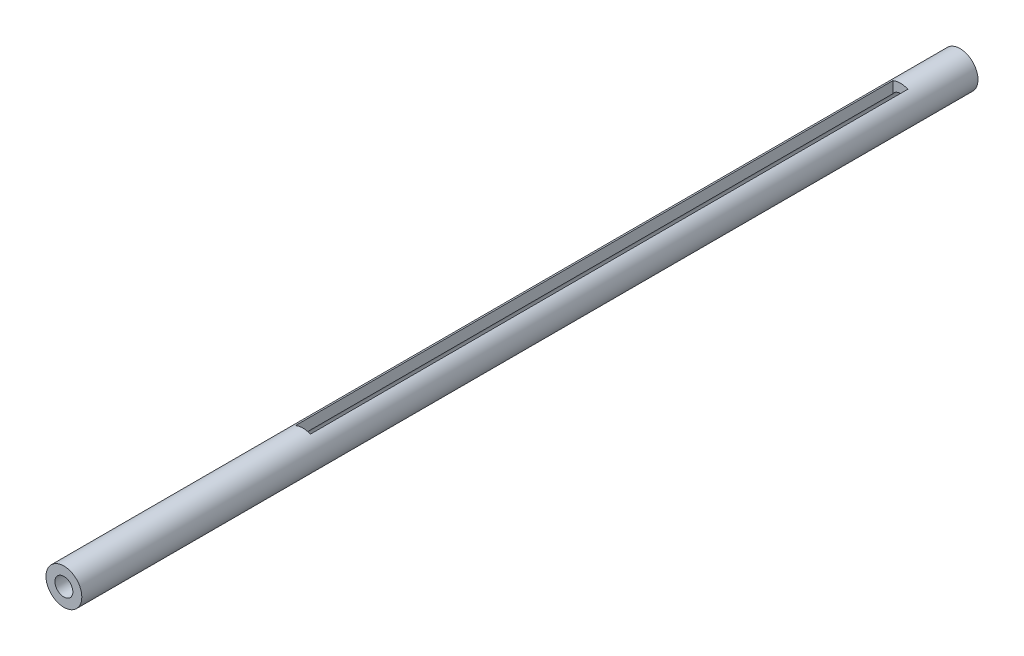
SolidWorks part; units mm, degrees
ref_plane "Front Plane" through (0, 0, 0) normal (0, 0, 1) x (1, 0, 0)
ref_plane "Top Plane" through (0, 0, 0) normal (0, 1, 0) x (1, 0, 0)
ref_plane "Right Plane" through (0, 0, 0) normal (1, 0, 0) x (0, 0, -1)
sketch "Sketch1" plane through (0, 0, 0) normal (0, 0, 1) x (1, 0, 0)
  circle A0 centre (0, 0) radius 1.5
  circle A1 centre (0, 0) radius 3
  dimension "D1" = 3
  dimension "D2" = 6
extrude "Boss-Extrude1" add sketch "Sketch1" along normal blind 150
sketch "Sketch2" plane through (0, 0, 0) normal (0, 1, 0) x (1, 0, 0)
  line L0 (-1.25, 110) -> (1.25, 110)
  line L1 (-1.25, 110) -> (-1.25, -110)
  line L2 (1.25, 110) -> (1.25, -110)
  line L3 (-1.25, -110) -> (1.25, -110)
  line L4 (-1.25, 110) -> (1.25, -110) construction
  line L5 (1.25, 110) -> (-1.25, -110) construction
  line L6 (-1.25, -10) -> (1.25, -10)
  point P1 (0, 0)
  dimension "D1" = 10
  dimension "D2" = 100
  dimension "D3" = 2.5
extrude "Cut-Extrude1" cut sketch "Sketch2" along normal blind 100 contours L6 L1 L3 L2
